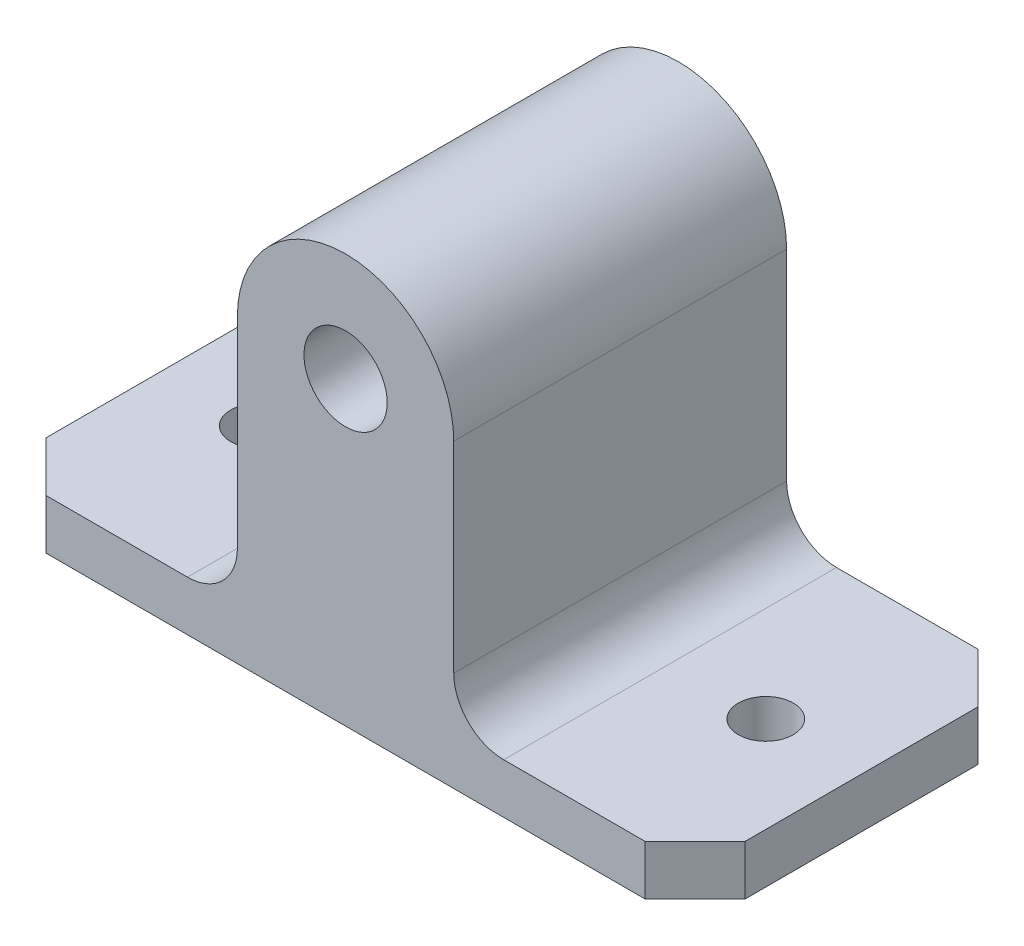
SolidWorks part; units mm, degrees
ref_plane "Front Plane" through (0, 0, 0) normal (0, 0, 1) x (1, 0, 0)
ref_plane "Top Plane" through (0, 0, 0) normal (0, 1, 0) x (1, 0, 0)
ref_plane "Right Plane" through (0, 0, 0) normal (1, 0, 0) x (0, 0, -1)
sketch "Sketch1" plane through (0, 0, 0) normal (0, 0, 1) x (1, 0, 0)
  line L0 (0, 0) -> (0, -18.0724) construction
  line L1 (-21, -18.0724) -> (21, -18.0724)
  line L2 (-21, -18.0724) -> (-21, -15.0724)
  line L3 (-21, -15.0724) -> (-9.5, -15.0724)
  line L4 (21, -18.0724) -> (21, -15.0724)
  line L6 (-6.5, 0) -> (-6.5, -12.0724)
  line L8 (6.5, 0) -> (6.5, -12.0724)
  line L9 (9.5, -15.0724) -> (21, -15.0724)
  circle A0 centre (0, 0) radius 2.5
  arc A1 (6.5, 0) -> (-6.5, 0) centre (0, 0) ccw
  arc A2 (9.5, -15.0724) -> (6.5, -12.0724) centre (9.5, -12.0724) cw
  arc A3 (-6.5, -12.0724) -> (-9.5, -15.0724) centre (-9.5, -12.0724) cw
  point P3 (9.3, 0)
  point P15 (6.5, -15.0724)
  dimension "D1" = 5
  dimension "D2" = 4
  dimension "D5" = 3
  dimension "D3" = 3
  dimension "D4" = 42
extrude "Boss-Extrude1" add sketch "Sketch1" along normal blind 20
chamfer "Chamfer1" distance 3 angle 45 4 edges at (-21, -16.5724, 20) (-21, -16.5724, 0) (21, -16.5724, 0) (21, -16.5724, 20)
sketch "Sketch2" plane through (0, -15.0724, 0) normal (0, 1, 0) x (1, 0, 0)
  line L0 (21, -10) -> (9.5, -10) construction
  line L1 (21, -17) -> (21, -3) construction
  line L2 (9.5, -20) -> (9.5, 0) construction
  line L3 (-9.5, -10) -> (-21, -10) construction
  line L4 (-9.5, -20) -> (-9.5, 0) construction
  line L5 (-21, -17) -> (-21, -3) construction
  circle A0 centre (15.25, -10) radius 1.65
  circle A1 centre (-15.25, -10) radius 1.65
  dimension "D1" = 3.3
  dimension "D2" = 3.3
extrude "Cut-Extrude1" cut sketch "Sketch2" against normal blind 20
